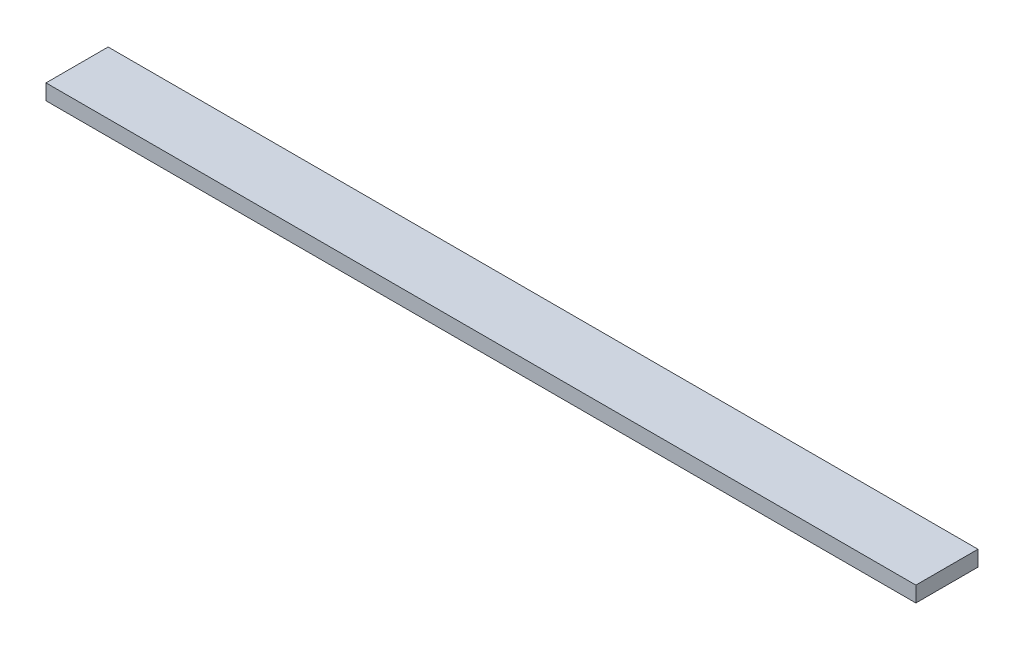
SolidWorks part; units mm, degrees
ref_plane "Front Plane" through (0, 0, 0) normal (0, 0, 1) x (1, 0, 0)
ref_plane "Top Plane" through (0, 0, 0) normal (0, 1, 0) x (1, 0, 0)
ref_plane "Right Plane" through (0, 0, 0) normal (1, 0, 0) x (0, 0, -1)
sketch "Sketch1" plane through (0, 0, 0) normal (0, 1, 0) x (1, 0, 0)
  line L1 (0, 0) -> (177.8, 0)
  line L2 (0, 0) -> (0, 12.7)
  line L3 (0, 12.7) -> (177.8, 12.7)
  line L4 (177.8, 0) -> (177.8, 12.7)
  dimension "D1" = 12.7
  dimension "D2" = 177.8
extrude "Boss-Extrude1" add sketch "Sketch1" along normal blind 3.175
